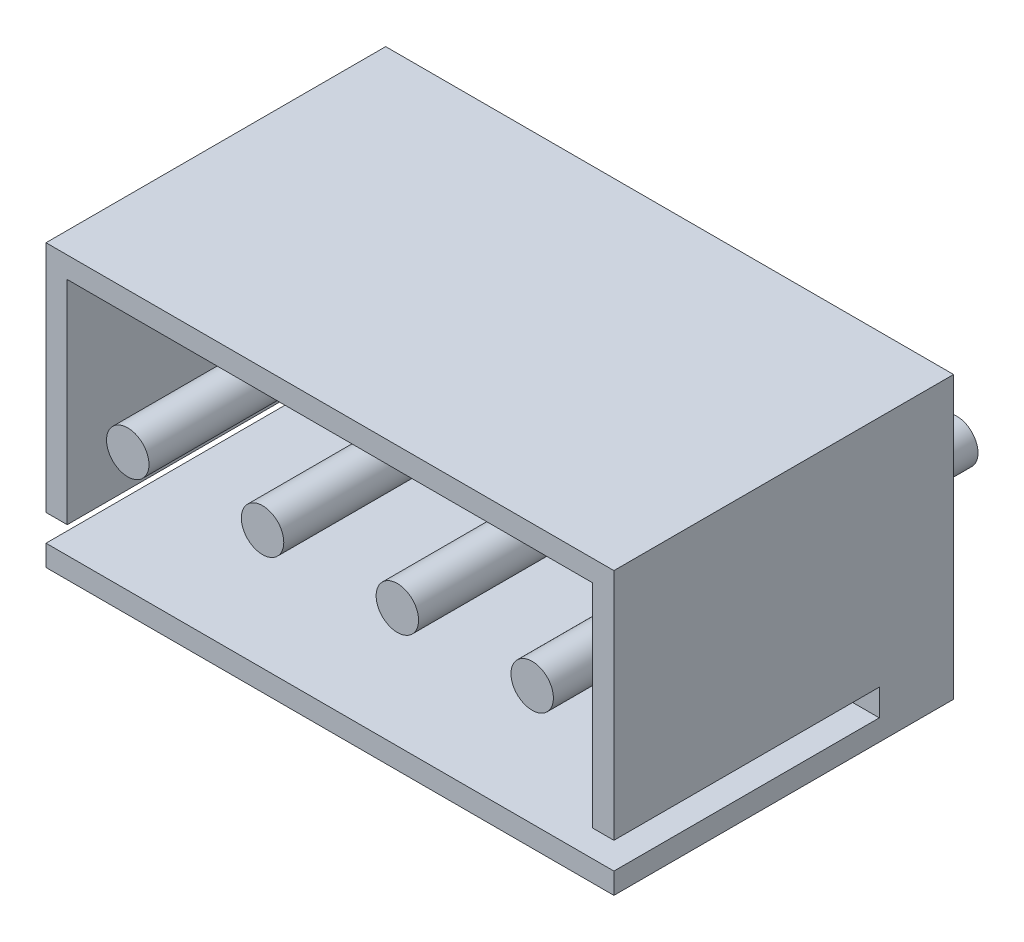
SolidWorks part; units mm, degrees
ref_plane "Спереди" through (0, 0, 0) normal (0, 0, 1) x (1, 0, 0)
ref_plane "Сверху" through (0, 0, 0) normal (0, 1, 0) x (1, 0, 0)
ref_plane "Справа" through (0, 0, 0) normal (1, 0, 0) x (0, 0, -1)
sketch "Эскиз1" plane through (0, 0, 0) normal (0, 0, 1) x (1, 0, 0)
  line L0 (0, 43.0382) -> (0, -41.0882) construction
  line L1 (-52.7879, 0) -> (56.1307, 0) construction
  line L3 (-5.35, 2.65) -> (5.35, 2.65)
  line L4 (-5.35, 2.65) -> (-5.35, -2.65)
  line L5 (-5.35, -2.65) -> (5.35, -2.65)
  line L6 (5.35, 2.65) -> (5.35, -2.65)
  dimension "D1" = 10.7
  dimension "D2" = 5.3
extrude "Вытянуть1" add sketch "Эскиз1" along normal blind 6.4
sketch "Эскиз2" plane through (0, 0, 6.4) normal (0, 0, 1) x (1, 0, 0)
  line L14 (-4.5773, 0) -> (3.2862, 0) construction
  line L15 (0, 1.6982) -> (0, -0.832) construction
  line L18 (-4.95, -2.25) -> (4.95, -2.25)
  line L19 (4.95, -2.25) -> (4.95, 2.25)
  line L20 (4.95, 2.25) -> (-4.95, 2.25)
  line L21 (-4.95, 2.25) -> (-4.95, -2.25)
  line L22 (-4.95, -2.25) -> (4.95, -2.25)
  line L23 (4.95, -2.25) -> (4.95, 2.25)
  line L24 (4.95, 2.25) -> (-4.95, 2.25)
  line L25 (-4.95, 2.25) -> (-4.95, -2.25)
  circle A0 centre (-1.27, 0) radius 0.4
  circle A1 centre (1.27, 0) radius 0.4
  circle A2 centre (-3.81, 0) radius 0.4
  circle A3 centre (3.81, 0) radius 0.4
  dimension "D2" = 2.54
  dimension "D3" = 0.8
  dimension "D4" = 2.54
  dimension "D1" = 0.4
extrude "Вырез-Вытянуть1" cut sketch "Эскиз2" against normal blind 5
sketch "Эскиз3" plane through (0, 0, 6.4) normal (0, 0, 1) x (1, 0, 0)
  line L1 (-6.5166, -2.2528) -> (6.3828, -2.2528)
  line L2 (-6.5166, -2.2528) -> (-6.5166, -1.7514)
  line L3 (-6.5166, -1.7514) -> (6.3828, -1.7514)
  line L4 (6.3828, -2.2528) -> (6.3828, -1.7514)
extrude "Вырез-Вытянуть2" cut sketch "Эскиз3" against normal up to surface (5 mm away) up to face at (3.41, 0, 1.4)
sketch "Эскиз4" plane through (0, 0, 6.4) normal (0, 0, 1) x (1, 0, 0)
  circle A1 centre (-1.27, 0) radius 0.4
  circle A2 centre (-1.27, 0) radius 0.4
  circle A3 centre (1.27, 0) radius 0.4
  circle A4 centre (1.27, 0) radius 0.4
  circle A5 centre (-3.81, 0) radius 0.4
  circle A6 centre (-3.81, 0) radius 0.4
  circle A7 centre (3.81, 0) radius 0.4
  circle A8 centre (3.81, 0) radius 0.4
  dimension "D1" = 0
  dimension "D2" = 0
  dimension "D3" = 0
  dimension "D4" = 0
extrude "Вытянуть2" add sketch "Эскиз4" against normal blind 8
